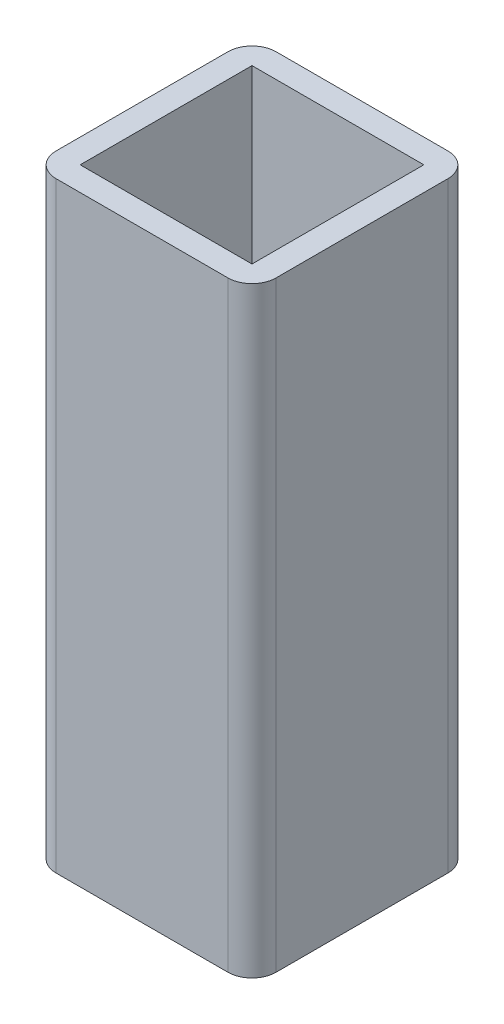
SolidWorks part; units mm, degrees
ref_plane "Front Plane" through (0, 0, 0) normal (0, 0, 1) x (1, 0, 0)
ref_plane "Top Plane" through (0, 0, 0) normal (0, 1, 0) x (1, 0, 0)
ref_plane "Right Plane" through (0, 0, 0) normal (1, 0, 0) x (0, 0, -1)
sketch "Sketch1" plane through (0, 0, 0) normal (0, 1, 0) x (1, 0, 0)
  line L1 (2.8, 0) -> (22.8, 0)
  line L2 (0, -2.8) -> (0, -22.8)
  line L3 (2.8, -25.6) -> (22.8, -25.6)
  line L4 (25.6, -2.8) -> (25.6, -22.8)
  arc A0 (22.8, 0) -> (25.6, -2.8) centre (22.8, -2.8) cw
  arc A1 (22.8, -25.6) -> (25.6, -22.8) centre (22.8, -22.8) ccw
  arc A2 (0, -22.8) -> (2.8, -25.6) centre (2.8, -22.8) ccw
  arc A3 (2.8, 0) -> (0, -2.8) centre (2.8, -2.8) ccw
  point P7 (25.6, 0)
  point P10 (25.6, -25.6)
  point P15 (0, 0)
  dimension "D2" = 2.8
  dimension "D1" = 25.6
extrude "Boss-Extrude1" add sketch "Sketch1" along normal blind 70
sketch "Sketch3" plane through (0, 0, 0) normal (0, -1, 0) x (-1, 0, 0)
  line L4 (-2.8, -2.8) -> (-22.8, -2.8)
  line L5 (-2.8, -2.8) -> (-2.8, -22.8)
  line L6 (-2.8, -22.8) -> (-22.8, -22.8)
  line L7 (-22.8, -2.8) -> (-22.8, -22.8)
  line L8 (-2.8, -2.8) -> (-22.8, -22.8) construction
  line L9 (-2.8, -22.8) -> (-22.8, -2.8) construction
  point P6 (-12.8, -12.8)
extrude "Cut-Extrude1" cut sketch "Sketch3" against normal blind 1040.5
